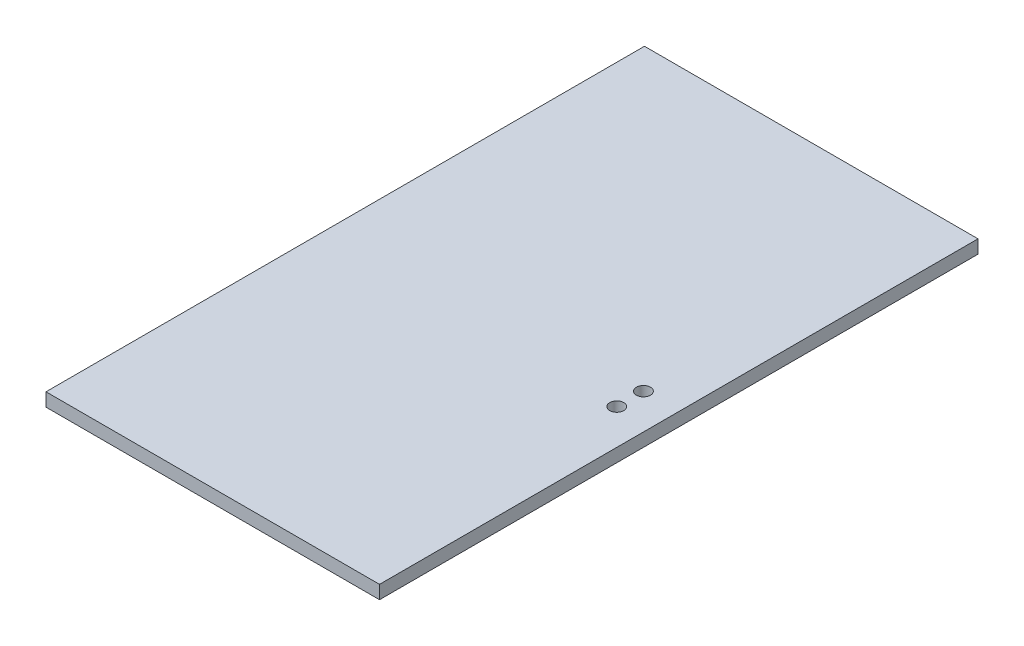
SolidWorks part; units mm, degrees
ref_plane "Front Plane" through (0, 0, 0) normal (0, 0, 1) x (1, 0, 0)
ref_plane "Top Plane" through (0, 0, 0) normal (0, 1, 0) x (1, 0, 0)
ref_plane "Right Plane" through (0, 0, 0) normal (1, 0, 0) x (0, 0, -1)
sketch "Sketch1" plane through (0, 0, 0) normal (1, 0, 0) x (0, 0, -1)
  line L1 (0, 0) -> (134.58, 0)
  line L2 (0, 0) -> (0, 3)
  line L3 (0, 3) -> (134.58, 3)
  line L4 (134.58, 0) -> (134.58, 3)
  dimension "D1" = 134.58
  dimension "D2" = 3
extrude "Boss-Extrude1" add sketch "Sketch1" along normal blind 75
sketch "Sketch2" plane through (0, 0, 0) normal (0, -1, 0) x (1, 0, 0)
  line L0 (0, 0) -> (0, -134.58) construction
  line L1 (0, -12.1) -> (3, -12.1)
  line L2 (0, -12.1) -> (0, -47.1)
  line L3 (0, -47.1) -> (3, -47.1)
  line L4 (3, -12.1) -> (3, -47.1)
  line L5 (75, 0) -> (0, 0) construction
  dimension "D1" = 12.1
  dimension "D2" = 3
  dimension "D3" = 35
extrude "Boss-Extrude2" add sketch "Sketch2" along normal blind 9
sketch "Sketch3" plane through (0, 0, 0) normal (-1, 0, 0) x (0, 0, 1)
  line L0 (-12.1, -9) -> (-47.1, -9) construction
  line L1 (-47.1, -9) -> (-47.1, 0) construction
  line L2 (-12.1, -9) -> (-12.1, 0) construction
  circle A0 centre (-23.7667, -4.5) radius 1.575
  circle A1 centre (-35.4333, -4.5) radius 1.575
  dimension "D1" = 3.15
  dimension "D2" = 3.15
  dimension "D3" = 4.5
  dimension "D4" = 4.5
  dimension "D5" = 11.6667
  dimension "D6" = 11.6667
extrude "Cut-Extrude1" cut sketch "Sketch3" against normal through all
sketch "Sketch5" plane through (0, 3, 0) normal (0, 1, 0) x (1, 0, 0)
  line L1 (75, 0) -> (0, 0) construction
  circle A0 centre (67.0592, 61.29) radius 1.575
  circle A1 centre (67.0592, 67.29) radius 1.575
  dimension "D1" = 3.15
  dimension "D2" = 3.15
  dimension "D3" = 6
  dimension "D4" = 61.29
extrude "Cut-Extrude2" cut sketch "Sketch5" against normal through all
